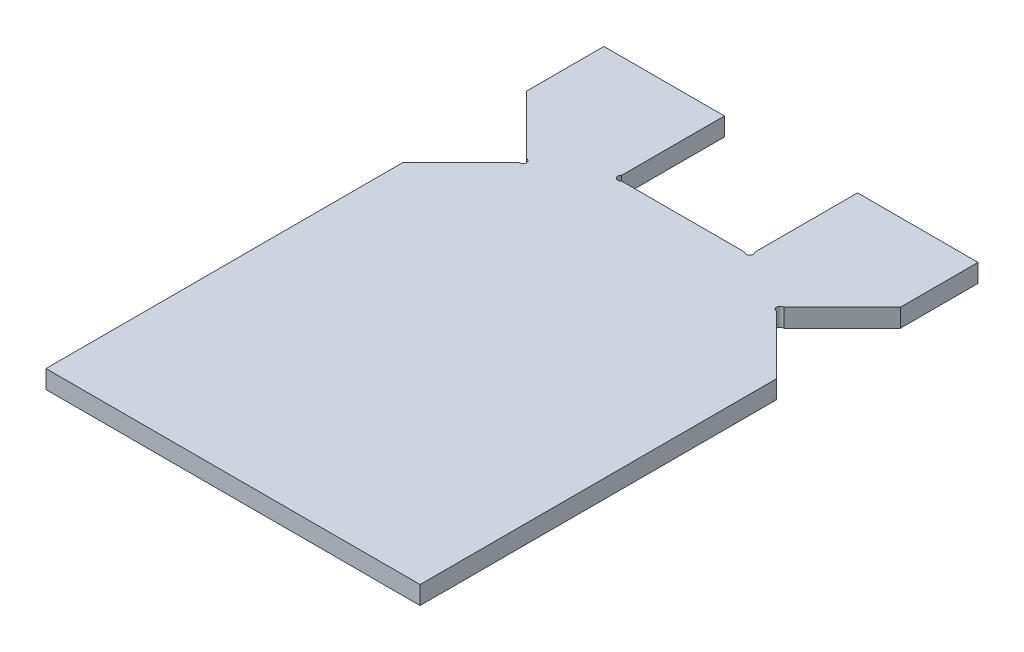
SolidWorks part; units mm, degrees
material "Pine"
ref_plane "Front Plane" through (0, 0, 0) normal (0, 0, 1) x (1, 0, 0)
ref_plane "Top Plane" through (0, 0, 0) normal (0, 1, 0) x (1, 0, 0)
ref_plane "Right Plane" through (0, 0, 0) normal (1, 0, 0) x (0, 0, -1)
sketch "Sketch1" plane through (0, 0, 0) normal (0, 1, 0) x (1, 0, 0)
  line L0 (-187.325, -558.8) -> (187.325, -558.8)
  line L1 (66.675, -107.95) -> (-66.675, -107.95)
  line L2 (66.675, -107.95) -> (66.675, 0)
  line L3 (66.675, 0) -> (-66.675, 0) construction
  line L4 (-66.675, -107.95) -> (-66.675, 0)
  line L5 (0, 0) -> (0, -107.95) construction
  line L6 (66.675, -53.975) -> (-66.675, -53.975) construction
  line L7 (-187.325, -558.8) -> (-187.325, 0)
  line L8 (-187.325, 0) -> (-66.675, 0)
  line L9 (187.325, -558.8) -> (187.325, 0)
  line L10 (187.325, 0) -> (66.675, 0)
  point P0 (0, -53.975)
  point P8 (0, -558.8)
  dimension "D1" = 107.95
  dimension "D2" = 133.35
  dimension "D3" = 450.85
  dimension "D4" = 374.65
extrude "Boss-Extrude1" add sketch "Sketch1" along normal blind 18.2562
sketch "Sketch2" plane through (0, 18.2562, 0) normal (0, 1, 0) x (1, 0, 0)
  line L0 (-187.325, -201.6125) -> (-125.4125, -139.7)
  line L1 (-187.325, 0) -> (-187.325, -558.8) construction
  line L2 (-125.4125, -139.7) -> (125.4125, -139.7) construction
  line L3 (125.4125, -139.7) -> (187.325, -201.6125)
  line L4 (187.325, -558.8) -> (187.325, 0) construction
  line L6 (-125.4125, -139.7) -> (-187.325, -77.7875)
  line L7 (-187.325, -77.7875) -> (-187.325, -201.6125)
  line L8 (125.4125, -139.7) -> (187.325, -77.7875)
  line L9 (187.325, -77.7875) -> (187.325, -201.6125)
  line L10 (-66.675, 0) -> (-187.325, 0) construction
  point P8 (0, -139.7)
  dimension "D1" = 77.7875
  dimension "D2" = 139.7
  dimension "D3" = 45
  dimension "D4" = 201.6125
extrude "Cut-Extrude1" cut sketch "Sketch2" against normal through all
hole_wizard "1/4 Clearance Hole1" positions "Sketch3" profile "Sketch4" hole size "1/4" standard "ANSI Inch" end condition up to next
sketch "Sketch3" plane through (0, 18.2562, 0) normal (0, 1, 0) x (1, 0, 0)
  line L3 (-128.7801, -139.7) -> (128.7801, -139.7) construction
  line L14 (-64.2938, -105.5688) -> (64.2938, -105.5688) construction
  line L15 (-125.4125, -139.7) -> (-187.325, -77.7875) construction
  line L16 (-187.325, -201.6125) -> (-125.4125, -139.7) construction
  line L17 (-66.675, -107.95) -> (-66.675, 0) construction
  line L18 (66.675, -107.95) -> (-66.675, -107.95) construction
  circle A0 centre (-128.7801, -139.7) radius 3.3782 construction
  circle A1 centre (-64.2938, -105.5688) radius 3.3782 construction
  point P13 (-64.2938, -105.5688)
  point P15 (64.2938, -105.5688)
  point P17 (-128.7801, -139.7)
  point P19 (128.7801, -139.7)
  point P39 (0, -139.7)
  point P73 (0, -105.5688)
  point P75 (0, 0)
  point P82 (-130.4365, -143.8792)
  point P85 (0, 0)
  dimension "D1" = 6.7564
  dimension "D2" = 2.3813
  dimension "D3" = 2.3813
  dimension "D4" = 2.3813
  dimension "D5" = 2.3813
sketch "Sketch4" plane through (-64.2938, 18.2562, 105.5688) normal (1, 0, 0) x (0, 0, 1)
  line L0 (0, 0) -> (0, 18.2562)
  line L1 (0, 18.2562) -> (3.5712, 18.2562)
  line L2 (3.5712, 18.2562) -> (3.5712, 0)
  line L5 (3.5712, 0) -> (0, 0)
  line L11 (0, -6.35) -> (0, 107.95) construction
  dimension "Thru Hole Dia." = 7.1425
  dimension "Thru Hole Depth" = 18.2562
